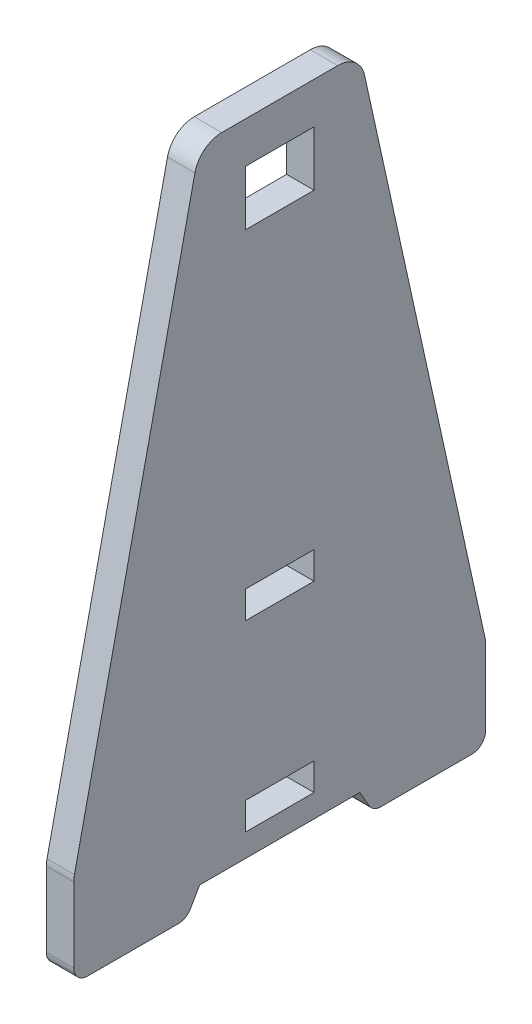
SolidWorks part; units mm, degrees
ref_plane "Ebene vorne" through (0, 0, 0) normal (0, 0, 1) x (1, 0, 0)
ref_plane "Ebene oben" through (0, 0, 0) normal (0, 1, 0) x (1, 0, 0)
ref_plane "Ebene rechts" through (0, 0, 0) normal (1, 0, 0) x (0, 0, -1)
sketch "Skizze1" plane through (0, 0, 0) normal (1, 0, 0) x (0, 0, -1)
  line L0 (0, 0) -> (0, 145) construction
  line L1 (17.5, 5) -> (-17.5, 5)
  line L2 (-17.5, 5) -> (-20.3868, 0)
  line L3 (-20.3868, 0) -> (-45, 0)
  line L4 (-45, 0) -> (-45, 20)
  line L5 (-45, 20) -> (-17.5, 145)
  line L6 (-17.5, 145) -> (17.5, 145)
  line L7 (45, 20) -> (17.5, 145)
  line L8 (45, 0) -> (45, 20)
  line L9 (20.3868, 0) -> (45, 0)
  line L10 (17.5, 5) -> (20.3868, 0)
  point P14 (0, 5)
  dimension "D1" = 35
  dimension "D2" = 145
  dimension "D3" = 20
  dimension "D4" = 90
  dimension "D5" = 35
  dimension "D6" = 120
  dimension "D7" = 5
extrude "Grundplatte" add sketch "Skizze1" along normal blind 6
sketch "Skizze2" plane through (6, 0, 0) normal (1, 0, 0) x (0, 0, -1)
  line L0 (0, 0) -> (0, 13) construction
  line L1 (0, 13) -> (0, 53) construction
  line L2 (0, 53) -> (0, 130) construction
  line L4 (7.5, 136) -> (-7.5, 136)
  line L5 (7.5, 136) -> (7.5, 124)
  line L6 (7.5, 124) -> (-7.5, 124)
  line L7 (-7.5, 136) -> (-7.5, 124)
  line L8 (7.5, 136) -> (-7.5, 124) construction
  line L9 (7.5, 124) -> (-7.5, 136) construction
  line L10 (7.5, 56) -> (-7.5, 56)
  line L11 (7.5, 56) -> (7.5, 50)
  line L12 (7.5, 50) -> (-7.5, 50)
  line L13 (-7.5, 56) -> (-7.5, 50)
  line L14 (7.5, 56) -> (-7.5, 50) construction
  line L15 (7.5, 50) -> (-7.5, 56) construction
  line L16 (7.5, 16) -> (-7.5, 16)
  line L17 (7.5, 16) -> (7.5, 10)
  line L18 (7.5, 10) -> (-7.5, 10)
  line L19 (-7.5, 16) -> (-7.5, 10)
  line L20 (7.5, 16) -> (-7.5, 10) construction
  line L21 (7.5, 10) -> (-7.5, 16) construction
  dimension "D1" = 15
  dimension "D2" = 6
  dimension "D3" = 6
  dimension "D4" = 12
  dimension "D5" = 13
  dimension "D6" = 40
  dimension "D7" = 120
extrude "Zapfendurchbruch" cut sketch "Skizze2" against normal through all
sketch "Skizze3" [suppressed] plane through (6, 0, 0) normal (1, 0, 0) x (0, 0, -1)
  line L0 (13.6409, 116) -> (25.0809, 64)
  line L1 (25.0809, 64) -> (0, 64)
  line L2 (0, 145) -> (0, 0) construction
  line L3 (17.5, 145) -> (-17.5, 145) construction
  line L4 (13.6409, 116) -> (-13.6409, 116)
  line L5 (-29.9209, 42) -> (29.9209, 42)
  line L6 (29.9209, 42) -> (33.8809, 24)
  line L7 (33.8809, 24) -> (-33.8809, 24)
  line L8 (45, 20) -> (17.5, 145) construction
  line L9 (-7.5, 124) -> (7.5, 124) construction
  line L10 (7.5, 56) -> (-7.5, 56) construction
  line L11 (-7.5, 50) -> (7.5, 50) construction
  line L12 (7.5, 16) -> (-7.5, 16) construction
  line L13 (-29.9209, 42) -> (-33.8809, 24)
  line L14 (-25.0809, 64) -> (0, 64)
  line L15 (-13.6409, 116) -> (-25.0809, 64)
  point P24 (0, 24)
  point P25 (0, 42)
  point P26 (0, 116)
  dimension "D1" = 8
  dimension "D2" = 8
  dimension "D3" = 8
  dimension "D4" = 8
  dimension "D5" = 10
extrude "Schnitt-Linear austragen1" [suppressed] cut sketch "Skizze3" against normal through all
fillet "Verrundung1" [suppressed] radius 6
fillet "Verrundung2" radius 3 4 edges at (3, 0, -45) (3, 0, -20.3868) (3, 0, 20.3868) (3, 0, 45)
fillet "Verrundung3" radius 6 4 edges at (3, 20, 45) (3, 145, 17.5) (3, 145, -17.5) (3, 20, -45)
